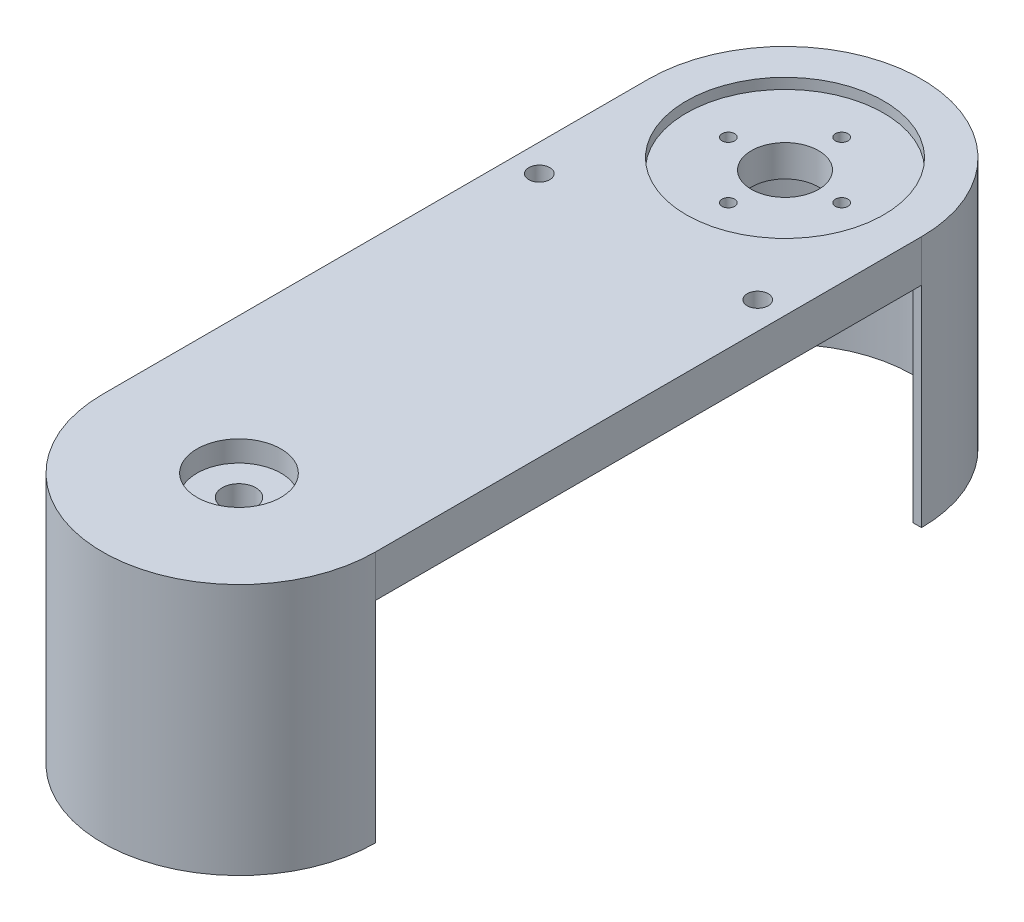
SolidWorks part; units mm, degrees
ref_plane "Front Plane" through (0, 0, 0) normal (0, 0, 1) x (1, 0, 0)
ref_plane "Top Plane" through (0, 0, 0) normal (0, 1, 0) x (1, 0, 0)
ref_plane "Right Plane" through (0, 0, 0) normal (1, 0, 0) x (0, 0, -1)
sketch "Sketch1" plane through (0, 0, 0) normal (0, 1, 0) x (1, 0, 0)
  line L0 (0, 97.5) -> (0, 65) construction
  line L2 (-32.5, 65) -> (-32.5, -65)
  line L4 (32.5, 65) -> (32.5, -65)
  line L5 (-27.4608, 82.3825) -> (27.4608, -82.3825) construction
  line L6 (-27.4608, -82.3825) -> (27.4608, 82.3825) construction
  line L7 (0, -97.5) -> (0, -65) construction
  arc A0 (-32.5, 65) -> (32.5, 65) centre (0, 65) cw
  arc A1 (32.5, -65) -> (-32.5, -65) centre (0, -65) cw
  point P0 (0, 0)
extrude "Boss-Extrude1" add sketch "Sketch1" along normal blind 10
sketch "Sketch2" plane through (0, 10, 0) normal (0, 1, 0) x (1, 0, 0)
  circle A0 centre (0, 65) radius 23.5
extrude "Cut-Extrude1" cut sketch "Sketch2" against normal blind 2.5
sketch "Sketch4" plane through (0, 7.5, 0) normal (0, 1, 0) x (1, 0, 0)
  circle A0 centre (0, 65) radius 8
extrude "Cut-Extrude3" cut sketch "Sketch4" against normal through all
sketch "Sketch7" plane through (0, 0, 0) normal (0, -1, 0) x (1, 0, 0)
  line L2 (32.5, -65) -> (32.5, 65)
  line L3 (-32.5, 65) -> (-32.5, -65)
  line L6 (-30.5, 65) -> (-32.5, 65)
  line L7 (30.5, 65) -> (32.5, 65)
  line L8 (-30.5, 65) -> (-30.5, -65) construction
  line L9 (-32.5, 65) -> (-32.5, -65) construction
  line L10 (32.5, -65) -> (32.5, 65) construction
  line L11 (30.5, -65) -> (30.5, 65) construction
  line L12 (-32.5, -65) -> (-30.5, -65)
  line L13 (30.5, -65) -> (32.5, -65)
  arc A0 (-30.5, -65) -> (30.5, -65) centre (0, -65) ccw
  arc A1 (30.5, 65) -> (-30.5, 65) centre (0, 65) ccw
  arc A2 (-32.5, -65) -> (32.5, -65) centre (0, -65) ccw
  arc A3 (32.5, 65) -> (-32.5, 65) centre (0, 65) ccw
  arc A4 (-32.5, -65) -> (32.5, -65) centre (0, -65) ccw
  arc A5 (32.5, 65) -> (-32.5, 65) centre (0, 65) ccw
  dimension "D1" = 0
  dimension "D2" = 2
extrude "Boss-Extrude3" add sketch "Sketch7" along normal blind 50
sketch "Sketch8" plane through (0, 7.5, 0) normal (0, 1, 0) x (1, 0, 0)
  circle A0 centre (0, 65) radius 13.5 construction
  circle A1 centre (13.5, 65) radius 1.5
  circle A2 centre (0, 78.5) radius 1.5
  circle A3 centre (-13.5, 65) radius 1.5
  circle A4 centre (0, 51.5) radius 1.5
extrude "Cut-Extrude4" cut sketch "Sketch8" against normal blind 10
sketch "Sketch9" plane through (0, 10, 0) normal (0, 1, 0) x (1, 0, 0)
  circle A0 centre (0, 65) radius 32.5 construction
  circle A1 centre (0, -65) radius 4
  point P8 (0, 0)
  point P9 (-2.9517, -70.9521)
  point P11 (0, 0)
extrude "Cut-Extrude5" cut sketch "Sketch9" against normal through all
sketch "Sketch10" plane through (0, 10, 0) normal (0, 1, 0) x (1, 0, 0)
  circle A0 centre (0, -65) radius 10
extrude "Cut-Extrude6" cut sketch "Sketch10" against normal blind 5
sketch "Sketch11" plane through (0, 10, 0) normal (0, 1, 0) x (1, 0, 0)
  line L0 (-26, 32.5) -> (26, 32.5) construction
  circle A0 centre (0, 65) radius 32.5 construction
  circle A1 centre (-26, 32.5) radius 2.5
  circle A2 centre (26, 32.5) radius 2.5
  point P7 (0, 32.5)
extrude "Cut-Extrude7" cut sketch "Sketch11" against normal through all
